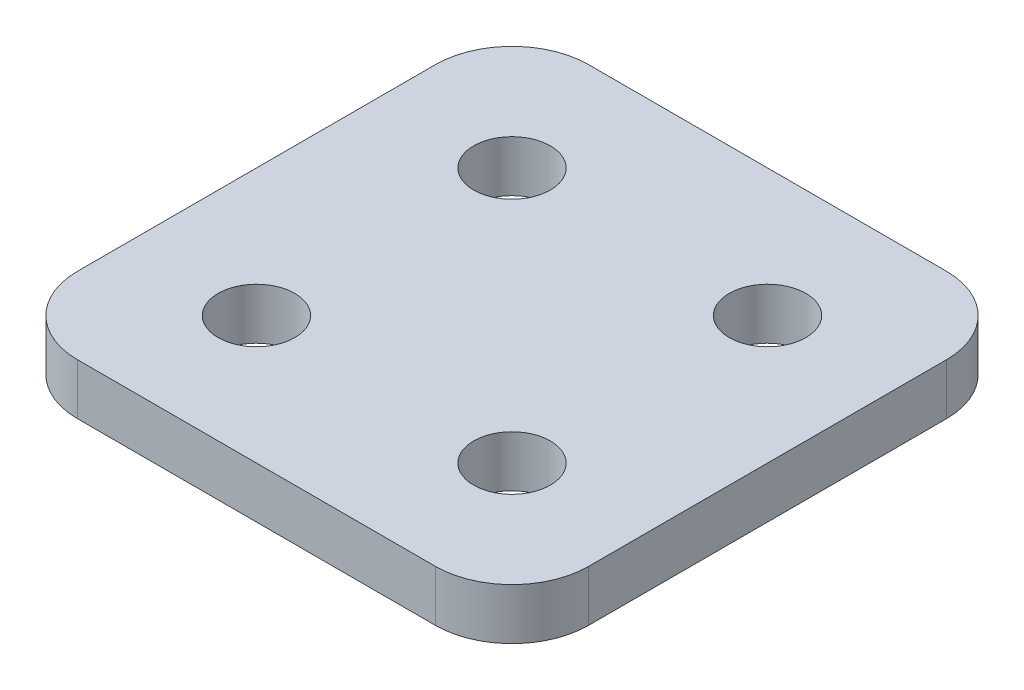
SolidWorks part; units mm, degrees
material "聚脂树脂"
ref_plane "前视基准面" through (0, 0, 0) normal (0, 0, 1) x (1, 0, 0)
ref_plane "上视基准面" through (0, 0, 0) normal (0, 1, 0) x (1, 0, 0)
ref_plane "右视基准面" through (0, 0, 0) normal (1, 0, 0) x (0, 0, -1)
sketch "草图1" plane through (0, 0, 0) normal (0, 1, 0) x (1, 0, 0)
  line L1 (-10, -10) -> (10, -10)
  line L2 (-10, -10) -> (-10, 10)
  line L3 (-10, 10) -> (10, 10)
  line L4 (10, -10) -> (10, 10)
  line L5 (-10, -10) -> (10, 10) construction
  line L6 (-10, 10) -> (10, -10) construction
  point P0 (0, 0)
  dimension "D1" = 20
  dimension "D2" = 20
extrude "凸台-拉伸1" add sketch "草图1" along normal blind 2
sketch "草图2" plane through (0, 2, 0) normal (0, 1, 0) x (1, 0, 0)
  line L1 (-5, -5) -> (5, -5) construction
  line L2 (-5, -5) -> (-5, 5) construction
  line L3 (-5, 5) -> (5, 5) construction
  line L4 (5, -5) -> (5, 5) construction
  line L5 (-5, -5) -> (5, 5) construction
  line L6 (-5, 5) -> (5, -5) construction
  circle A0 centre (-5, 5) radius 1.5
  circle A1 centre (5, 5) radius 1.5
  circle A2 centre (-5, -5) radius 1.5
  circle A3 centre (5, -5) radius 1.5
  point P0 (0, 0)
  point P7 (4.8143, -5)
  point P9 (5.1803, 5)
  point P13 (-5.2085, -5)
  dimension "D3" = 3
  dimension "D1" = 10
  dimension "D2" = 10
extrude "切除-拉伸1" cut sketch "草图2" against normal through all
fillet "圆角1" radius 3 4 edges at (-10, 1, -10) (10, 1, -10) (10, 1, 10) (-10, 1, 10)
